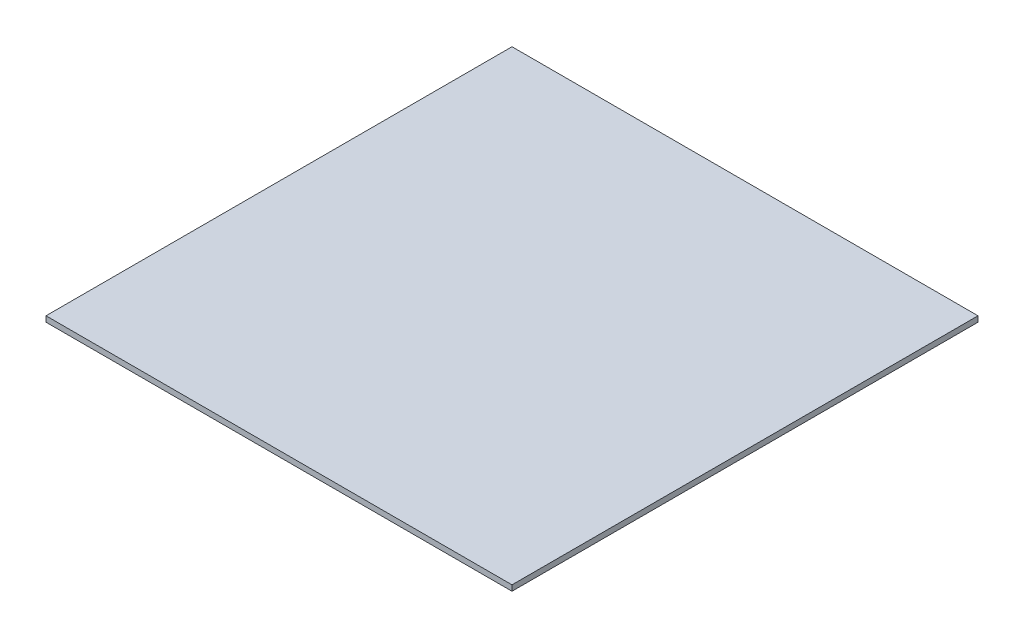
SolidWorks part; units mm, degrees
material "PE High Density"
ref_plane "Front Plane" through (0, 0, 0) normal (0, 0, 1) x (1, 0, 0)
ref_plane "Top Plane" through (0, 0, 0) normal (0, 1, 0) x (1, 0, 0)
ref_plane "Right Plane" through (0, 0, 0) normal (1, 0, 0) x (0, 0, -1)
sketch "Sketch1" plane through (0, 0, 0) normal (0, 1, 0) x (1, 0, 0)
  line L0 (-125, 125) -> (125, 125)
  line L1 (-125, 125) -> (-125, -125)
  line L2 (125, 125) -> (125, -125)
  line L3 (-125, -125) -> (125, -125)
  line L4 (-125, 125) -> (125, -125) construction
  line L5 (125, 125) -> (-125, -125) construction
  point P0 (0, 0)
  point P1 (0, 0)
  dimension "D1" = 250
  dimension "D2" = 250
extrude "Boss-Extrude1" add sketch "Sketch1" along normal blind 3
